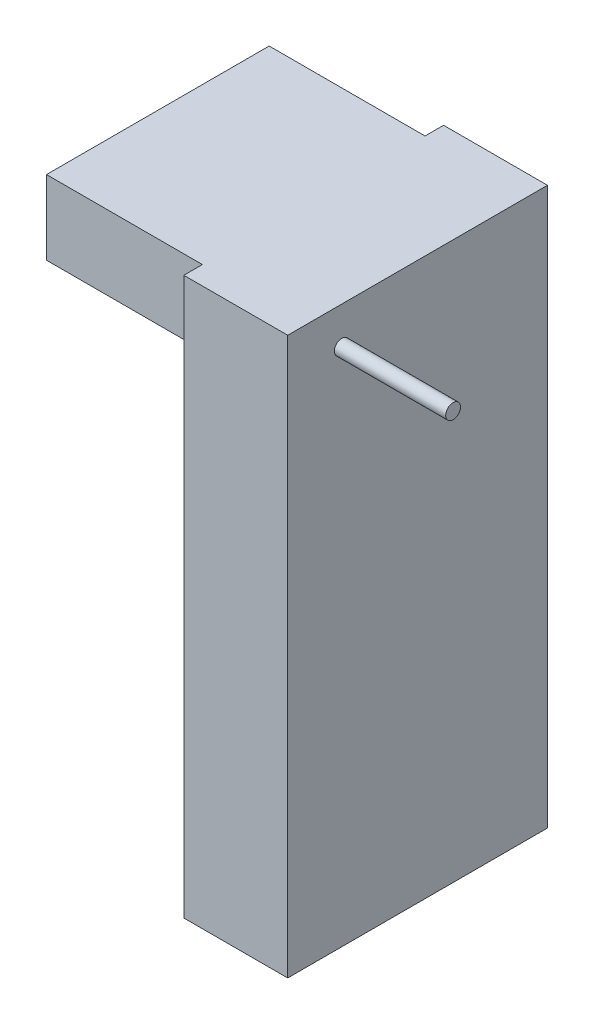
SolidWorks part; units mm, degrees
ref_plane "Plan de face" through (0, 0, 0) normal (0, 0, 1) x (1, 0, 0)
ref_plane "Plan de dessus" through (0, 0, 0) normal (0, 1, 0) x (1, 0, 0)
ref_plane "Plan de droite" through (0, 0, 0) normal (1, 0, 0) x (0, 0, -1)
sketch "Esquisse1" plane through (0, 0, 0) normal (1, 0, 0) x (0, 0, -1)
  line L1 (8.6683, 3.6035) -> (38.6683, 3.6035)
  line L2 (8.6683, 3.6035) -> (8.6683, -6.3965)
  line L3 (8.6683, -6.3965) -> (38.6683, -6.3965)
  line L4 (38.6683, 3.6035) -> (38.6683, -6.3965)
  dimension "D2" = 10
  dimension "D3" = 30
extrude "Boss.-Extru.1" add sketch "Esquisse1" along normal blind 35
sketch "Esquisse3" plane through (35, 0, 0) normal (1, 0, 0) x (0, 0, -1)
  line L0 (38.6683, 3.6035) -> (8.6683, 3.6035) construction
  circle A0 centre (13.4503, -1.3965) radius 1
  dimension "D1" = 2
  dimension "D2" = 5
extrude "Boss.-Extru.2" add sketch "Esquisse3" along normal blind 15
sketch "Esquisse4" plane through (35, 0, 0) normal (1, 0, 0) x (0, 0, -1)
  line L0 (8.6683, 3.6035) -> (8.6683, -6.3965) construction
  line L1 (6.1683, 3.6035) -> (41.1683, 3.6035)
  line L2 (6.1683, 3.6035) -> (6.1683, -71.3965)
  line L3 (6.1683, -71.3965) -> (41.1683, -71.3965)
  line L4 (41.1683, 3.6035) -> (41.1683, -71.3965)
  dimension "D1" = 35
  dimension "D2" = 2.5
  dimension "D3" = 75
extrude "Boss.-Extru.3" add sketch "Esquisse4" against normal blind 14
